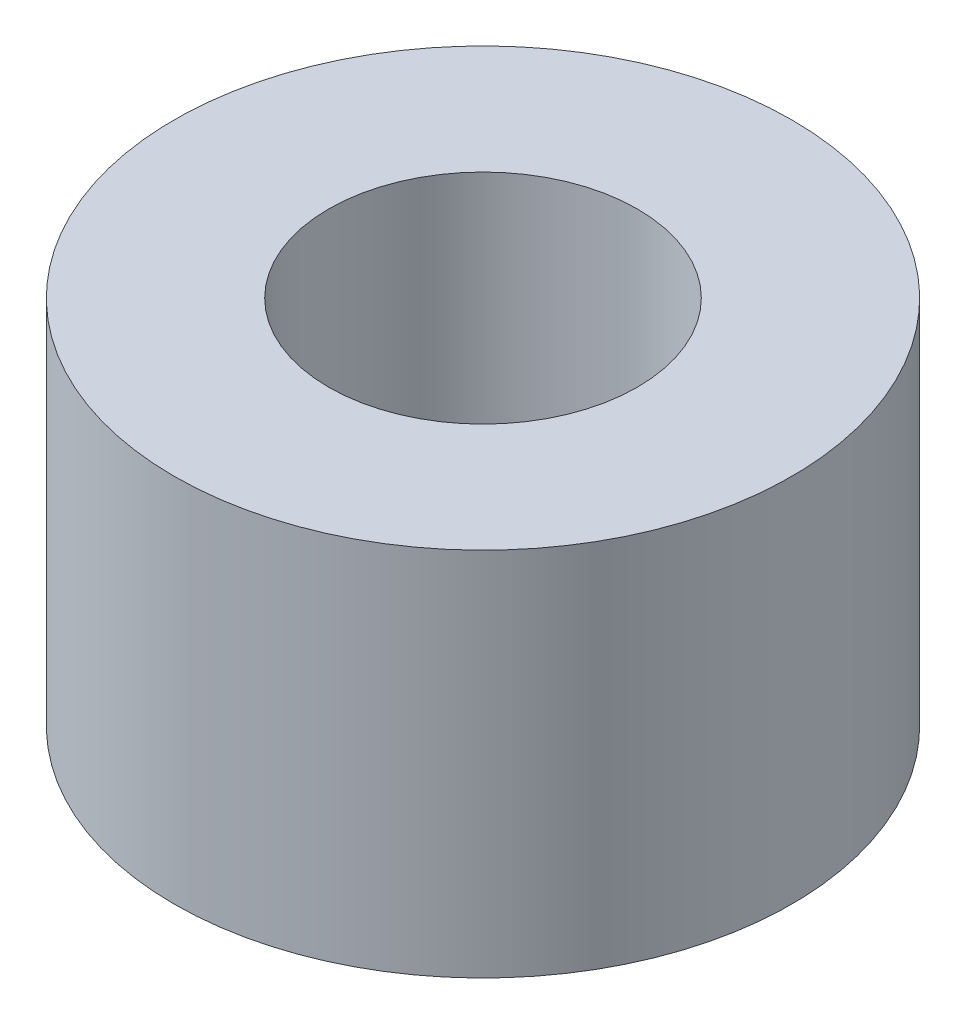
SolidWorks part; units mm, degrees
ref_plane "Front Plane" through (0, 0, 0) normal (0, 0, 1) x (1, 0, 0)
ref_plane "Top Plane" through (0, 0, 0) normal (0, 1, 0) x (1, 0, 0)
ref_plane "Right Plane" through (0, 0, 0) normal (1, 0, 0) x (0, 0, -1)
sketch "Sketch1" plane through (0, 0, 0) normal (0, 1, 0) x (1, 0, 0)
  circle A0 centre (0, 0) radius 5
  circle A1 centre (0, 0) radius 2.5
  dimension "D1" = 5
  dimension "D2" = 10
extrude "Boss-Extrude1" add sketch "Sketch1" along normal blind 6
